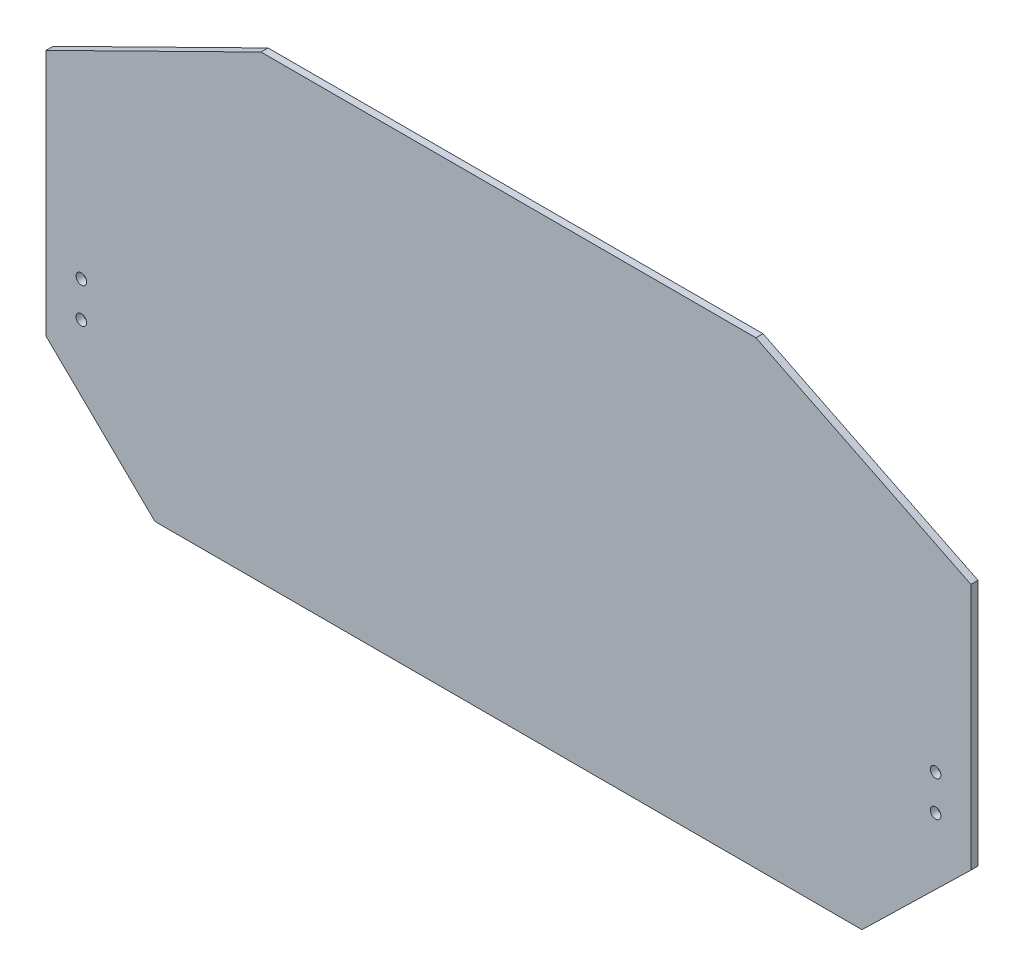
SolidWorks part; units mm, degrees
ref_plane "前视基准面" through (0, 0, 0) normal (0, 0, 1) x (1, 0, 0)
ref_plane "上视基准面" through (0, 0, 0) normal (0, 1, 0) x (1, 0, 0)
ref_plane "右视基准面" through (0, 0, 0) normal (1, 0, 0) x (0, 0, -1)
sketch "草图1" plane through (0, 0, 0) normal (0, 0, 1) x (1, 0, 0)
  line L0 (-130.8148, 0) -> (-130.8148, 70)
  line L1 (-130.8148, 70) -> (-70, 100)
  line L2 (-70, 100) -> (70, 100)
  line L3 (0, 0) -> (0, 100) construction
  line L4 (-130.8148, 0) -> (0, 0) construction
  line L5 (130.8148, 0) -> (130.8148, 70)
  line L6 (130.8148, 70) -> (70, 100)
  line L7 (-130.8148, 0) -> (-100, -30)
  line L8 (-100, -30) -> (100, -30)
  line L9 (130.8148, 0) -> (100, -30)
  line L10 (-120.8148, 0) -> (-120.8148, 9) construction
  line L11 (-130.8148, 0) -> (0, -130.8148) construction
  line L12 (0, -130.8148) -> (130.8148, 0) construction
  line L13 (0, 0) -> (0, -130.8148) construction
  line L14 (-120.8148, 9) -> (-120.8148, 19) construction
  circle A0 centre (-120.8148, 9) radius 1.5
  circle A1 centre (120.8148, 9) radius 1.5
  circle A2 centre (-120.8148, 19) radius 1.5
  circle A3 centre (120.8148, 19) radius 1.5
  point P12 (0, -30)
  dimension "D1" = 3
  dimension "D2" = 185
  dimension "D3" = 100
  dimension "D4" = 70
  dimension "D5" = 30
  dimension "D6" = 200
  dimension "D7" = 140
  dimension "D8" = 9
  dimension "D9" = 10
  dimension "D11" = 10
  dimension "D10" = 2
extrude "凸台-拉伸1" add sketch "草图1" along normal blind 2
